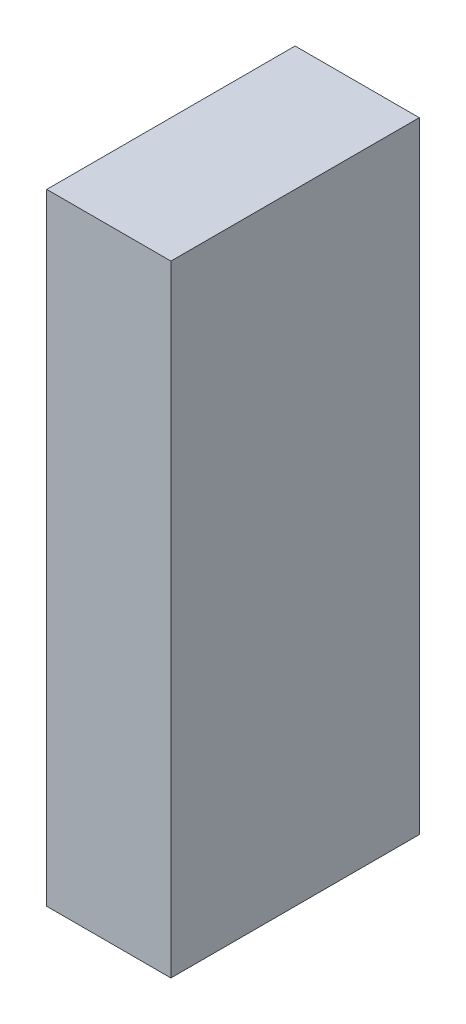
SolidWorks part; units mm, degrees
ref_plane "Front Plane" through (0, 0, 0) normal (0, 0, 1) x (1, 0, 0)
ref_plane "Top Plane" through (0, 0, 0) normal (0, 1, 0) x (1, 0, 0)
ref_plane "Right Plane" through (0, 0, 0) normal (1, 0, 0) x (0, 0, -1)
sketch "Sketch1" plane through (0, 0, 0) normal (0, 0, 1) x (1, 0, 0)
  line L1 (0, 0) -> (20, 0)
  line L2 (0, 0) -> (0, 100)
  line L3 (0, 100) -> (20, 100)
  line L4 (20, 0) -> (20, 100)
  dimension "D1" = 100
  dimension "D2" = 20
extrude "Boss-Extrude1" add sketch "Sketch1" along normal blind 40
